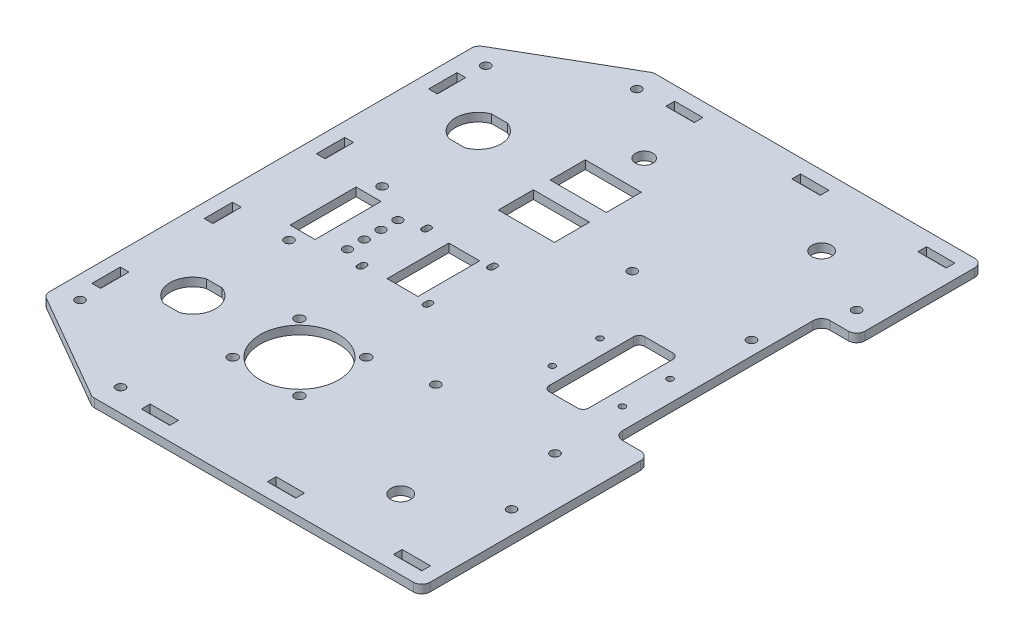
SolidWorks part; units mm, degrees
ref_plane "Front Plane" through (0, 0, 0) normal (0, 0, 1) x (1, 0, 0)
ref_plane "Top Plane" through (0, 0, 0) normal (0, 1, 0) x (1, 0, 0)
ref_plane "Right Plane" through (0, 0, 0) normal (1, 0, 0) x (0, 0, -1)
sketch "Sketch1" plane through (0, 0, 0) normal (0, 1, 0) x (1, 0, 0)
  line L0 (-85, 100) -> (85, 100) construction
  line L1 (-125, 100) -> (125, 100) construction
  line L2 (-125, 100) -> (-125, -100) construction
  line L3 (-125, -100) -> (125, -100) construction
  line L4 (125, 100) -> (125, -100) construction
  line L5 (85, 100) -> (125, 76.906) construction
  line L6 (125, 76.906) -> (125, -76.906) construction
  line L8 (-125, -76.906) -> (-125, 76.906) construction
  line L9 (-125, 76.906) -> (-85, 100) construction
  line L10 (-125, 0) -> (125, 0) construction
  line L11 (85, -100) -> (125, -76.906) construction
  line L12 (-85, -100) -> (85, -100) construction
  line L13 (-125, -76.906) -> (-85, -100) construction
  line L15 (-42.5, 100) -> (42.5, 100) construction
  line L16 (-42.5, 100) -> (-42.5, 65) construction
  line L17 (-42.5, 65) -> (42.5, 65) construction
  line L18 (42.5, 100) -> (42.5, 65) construction
  line L19 (42.5, -100) -> (42.5, -65) construction
  line L20 (-42.5, -65) -> (42.5, -65) construction
  line L21 (-42.5, -100) -> (-42.5, -65) construction
  line L22 (-42.5, -100) -> (42.5, -100) construction
  line L41 (32.5, -100) -> (32.5, 100)
  line L42 (-85, 100) -> (-125, 76.906)
  line L43 (-125, 76.906) -> (-125, -76.906)
  line L44 (-125, -76.906) -> (-85, -100)
  line L45 (-85, -100) -> (32.5, -100)
  line L46 (32.5, 100) -> (-85, 100)
  line L59 (-57.851, 11) -> (-68.851, 11) construction
  line L60 (-57.851, -11) -> (-57.851, 11) construction
  line L61 (-68.851, 11) -> (-68.851, -11) construction
  line L62 (-68.851, -11) -> (-57.851, -11) construction
  line L63 (-54.901, 12.05) -> (-54.901, 10.95) construction
  line L64 (-52.701, 10.95) -> (-52.701, 12.05) construction
  line L65 (-54.901, -10.95) -> (-54.901, -12.05) construction
  line L66 (-52.701, -12.05) -> (-52.701, -10.95) construction
  line L67 (-78.401, -10.95) -> (-78.401, -12.05) construction
  line L68 (-76.201, -12.05) -> (-76.201, -10.95) construction
  line L69 (-78.401, 12.05) -> (-78.401, 10.95) construction
  line L70 (-76.201, 10.95) -> (-76.201, 12.05) construction
  line L71 (-68.851, -11) -> (-57.851, -11)
  line L72 (-57.851, -11) -> (-57.851, 11)
  line L73 (-68.851, 11) -> (-68.851, -11)
  line L74 (-57.851, 11) -> (-68.851, 11)
  line L75 (-76.201, -12.05) -> (-76.201, -10.95)
  line L76 (-78.401, -10.95) -> (-78.401, -12.05)
  line L77 (-54.901, -10.95) -> (-54.901, -12.05)
  line L78 (-52.701, -12.05) -> (-52.701, -10.95)
  line L79 (-52.701, 10.95) -> (-52.701, 12.05)
  line L80 (-54.901, 12.05) -> (-54.901, 10.95)
  line L81 (-76.201, 10.95) -> (-76.201, 12.05)
  line L82 (-78.401, 12.05) -> (-78.401, 10.95)
  arc A16 (-52.701, 12.05) -> (-54.901, 12.05) centre (-53.801, 12.05) ccw construction
  arc A17 (-54.901, 10.95) -> (-52.701, 10.95) centre (-53.801, 10.95) ccw construction
  arc A18 (-52.701, -10.95) -> (-54.901, -10.95) centre (-53.801, -10.95) ccw construction
  arc A19 (-54.901, -12.05) -> (-52.701, -12.05) centre (-53.801, -12.05) ccw construction
  arc A20 (-76.201, -10.95) -> (-78.401, -10.95) centre (-77.301, -10.95) ccw construction
  arc A21 (-78.401, -12.05) -> (-76.201, -12.05) centre (-77.301, -12.05) ccw construction
  arc A22 (-76.201, 12.05) -> (-78.401, 12.05) centre (-77.301, 12.05) ccw construction
  arc A23 (-78.401, 10.95) -> (-76.201, 10.95) centre (-77.301, 10.95) ccw construction
  arc A24 (-78.401, -12.05) -> (-76.201, -12.05) centre (-77.301, -12.05) ccw
  arc A25 (-76.201, -10.95) -> (-78.401, -10.95) centre (-77.301, -10.95) ccw
  arc A26 (-54.901, -12.05) -> (-52.701, -12.05) centre (-53.801, -12.05) ccw
  arc A27 (-52.701, -10.95) -> (-54.901, -10.95) centre (-53.801, -10.95) ccw
  arc A28 (-54.901, 10.95) -> (-52.701, 10.95) centre (-53.801, 10.95) ccw
  arc A29 (-52.701, 12.05) -> (-54.901, 12.05) centre (-53.801, 12.05) ccw
  arc A30 (-78.401, 10.95) -> (-76.201, 10.95) centre (-77.301, 10.95) ccw
  arc A31 (-76.201, 12.05) -> (-78.401, 12.05) centre (-77.301, 12.05) ccw
  circle A32 centre (-98.226, -16.6) radius 1.6 construction
  circle A33 centre (-98.226, 16.6) radius 1.6 construction
  circle A34 centre (-98.226, -16.6) radius 1.6
  circle A35 centre (-98.226, 16.6) radius 1.6
  spline S0 degree 3 poles (-50.026, -38.959) (-50.026, -42.359) (-46.626, -42.359) (-46.626, -38.959) (-46.626, -35.559) (-50.026, -35.559) (-50.026, -38.959) (-50.026, -42.359) (-46.626, -42.359) knots -0.5 0 0 0 0.5 0.5 0.5 1 1 1 1.5 1.5 1.5 weights 1 0.333333 0.333333 1 0.333333 0.333333 1 0.333333 0.333333 only from (-50.026, -38.959) to (-50.026, -38.959) construction
  spline S1 degree 3 poles (-50.026, -62.759) (-50.026, -66.159) (-46.626, -66.159) (-46.626, -62.759) (-46.626, -59.359) (-50.026, -59.359) (-50.026, -62.759) (-50.026, -66.159) (-46.626, -66.159) knots -0.5 0 0 0 0.5 0.5 0.5 1 1 1 1.5 1.5 1.5 weights 1 0.333333 0.333333 1 0.333333 0.333333 1 0.333333 0.333333 only from (-50.026, -62.759) to (-50.026, -62.759) construction
  spline S2 degree 3 poles (-73.826, -62.759) (-73.826, -66.159) (-70.426, -66.159) (-70.426, -62.759) (-70.426, -59.359) (-73.826, -59.359) (-73.826, -62.759) (-73.826, -66.159) (-70.426, -66.159) knots -0.5 0 0 0 0.5 0.5 0.5 1 1 1 1.5 1.5 1.5 weights 1 0.333333 0.333333 1 0.333333 0.333333 1 0.333333 0.333333 only from (-73.826, -62.759) to (-73.826, -62.759) construction
  spline S3 degree 3 poles (-73.826, -38.959) (-73.826, -42.359) (-70.426, -42.359) (-70.426, -38.959) (-70.426, -35.559) (-73.826, -35.559) (-73.826, -38.959) (-73.826, -42.359) (-70.426, -42.359) knots -0.5 0 0 0 0.5 0.5 0.5 1 1 1 1.5 1.5 1.5 weights 1 0.333333 0.333333 1 0.333333 0.333333 1 0.333333 0.333333 only from (-73.826, -38.959) to (-73.826, -38.959) construction
  spline S4 degree 3 poles (-50.026, -38.959) (-50.026, -42.359) (-46.626, -42.359) (-46.626, -38.959) (-46.626, -35.559) (-50.026, -35.559) (-50.026, -38.959) (-50.026, -42.359) (-46.626, -42.359) knots -0.5 0 0 0 0.5 0.5 0.5 1 1 1 1.5 1.5 1.5 weights 1 0.333333 0.333333 1 0.333333 0.333333 1 0.333333 0.333333 only from (-50.026, -38.959) to (-50.026, -38.959)
  spline S5 degree 3 poles (-50.026, -62.759) (-50.026, -66.159) (-46.626, -66.159) (-46.626, -62.759) (-46.626, -59.359) (-50.026, -59.359) (-50.026, -62.759) (-50.026, -66.159) (-46.626, -66.159) knots -0.5 0 0 0 0.5 0.5 0.5 1 1 1 1.5 1.5 1.5 weights 1 0.333333 0.333333 1 0.333333 0.333333 1 0.333333 0.333333 only from (-50.026, -62.759) to (-50.026, -62.759)
  spline S6 degree 3 poles (-73.826, -62.759) (-73.826, -66.159) (-70.426, -66.159) (-70.426, -62.759) (-70.426, -59.359) (-73.826, -59.359) (-73.826, -62.759) (-73.826, -66.159) (-70.426, -66.159) knots -0.5 0 0 0 0.5 0.5 0.5 1 1 1 1.5 1.5 1.5 weights 1 0.333333 0.333333 1 0.333333 0.333333 1 0.333333 0.333333 only from (-73.826, -62.759) to (-73.826, -62.759)
  spline S7 degree 3 poles (-73.826, -38.959) (-73.826, -42.359) (-70.426, -42.359) (-70.426, -38.959) (-70.426, -35.559) (-73.826, -35.559) (-73.826, -38.959) (-73.826, -42.359) (-70.426, -42.359) knots -0.5 0 0 0 0.5 0.5 0.5 1 1 1 1.5 1.5 1.5 weights 1 0.333333 0.333333 1 0.333333 0.333333 1 0.333333 0.333333 only from (-73.826, -38.959) to (-73.826, -38.959)
  spline S8 degree 3 poles (-72.8629, -56.8847) (-73.764, -54.9949) (-74.226, -52.9527) (-74.226, -50.859) knots 0 0 0 0 1 1 1 1 weights 1 0.98357 0.98357 1 construction
  spline S9 degree 3 poles (-72.8629, -56.8847) (-72.5466, -57.548) (-72.1792, -58.1844) (-71.7629, -58.79) knots 0 0 0 0 1 1 1 1 weights 1 0.997939 0.997939 1 construction
  spline S10 degree 3 poles (-48.6891, -58.79) (-54.8172, -67.7043) (-65.6348, -67.7043) (-71.7629, -58.79) knots 0 0 0 0 1 1 1 1 weights 1 0.710999 0.710999 1 construction
  spline S11 degree 3 poles (-48.6891, -58.79) (-48.2728, -58.1844) (-47.9054, -57.548) (-47.5891, -56.8847) knots 0 0 0 0 1 1 1 1 weights 1 0.997939 0.997939 1 construction
  spline S12 degree 3 poles (-59.126, -36.9023) (-59.8586, -36.8445) (-60.5934, -36.8445) (-61.326, -36.9023) knots 0 0 0 0 1 1 1 1 weights 1 0.997939 0.997939 1 construction
  spline S13 degree 3 poles (-59.126, -36.9023) (-48.3419, -37.7522) (-42.9332, -47.1205) (-47.5891, -56.8847) knots 0 0 0 0 1 1 1 1 weights 1 0.710999 0.710999 1 construction
  spline S14 degree 3 poles (-74.226, -50.859) (-74.226, -43.1606) (-69.0006, -37.5072) (-61.326, -36.9023) knots 0 0 0 0 1 1 1 1 weights 1 0.822907 0.822907 1 construction
  spline S15 degree 3 poles (-72.8629, -56.8847) (-73.764, -54.9949) (-74.226, -52.9527) (-74.226, -50.859) knots 0 0 0 0 1 1 1 1 weights 1 0.98357 0.98357 1
  spline S16 degree 3 poles (-72.8629, -56.8847) (-72.5466, -57.548) (-72.1792, -58.1844) (-71.7629, -58.79) knots 0 0 0 0 1 1 1 1 weights 1 0.997939 0.997939 1
  spline S17 degree 3 poles (-48.6891, -58.79) (-54.8172, -67.7043) (-65.6348, -67.7043) (-71.7629, -58.79) knots 0 0 0 0 1 1 1 1 weights 1 0.710999 0.710999 1
  spline S18 degree 3 poles (-48.6891, -58.79) (-48.2728, -58.1844) (-47.9054, -57.548) (-47.5891, -56.8847) knots 0 0 0 0 1 1 1 1 weights 1 0.997939 0.997939 1
  spline S19 degree 3 poles (-59.126, -36.9023) (-59.8586, -36.8445) (-60.5934, -36.8445) (-61.326, -36.9023) knots 0 0 0 0 1 1 1 1 weights 1 0.997939 0.997939 1
  spline S20 degree 3 poles (-59.126, -36.9023) (-48.3419, -37.7522) (-42.9332, -47.1205) (-47.5891, -56.8847) knots 0 0 0 0 1 1 1 1 weights 1 0.710999 0.710999 1
  spline S21 degree 3 poles (-74.226, -50.859) (-74.226, -43.1606) (-69.0006, -37.5072) (-61.326, -36.9023) knots 0 0 0 0 1 1 1 1 weights 1 0.822907 0.822907 1
  point P4 (0, 100)
  point P6 (-125, 0)
  point P9 (0, 0)
  point P22 (0, 65)
  dimension "D1" = 250
  dimension "D2" = 200
  dimension "D3" = 60
  dimension "D4" = 60
  dimension "D5" = 40
  dimension "D6" = 85
  dimension "D7" = 35
  dimension "D8" = 20
extrude "Boss-Extrude1" add sketch "Sketch1" along normal blind 3
sketch "Sketch5" plane through (0, 3, 0) normal (0, 1, 0) x (1, 0, 0)
  line L0 (32.5, -40) -> (-32.5, -40) construction
  line L1 (32.5, 40) -> (-32.5, 40) construction
  line L2 (32.5, 40) -> (32.5, -40) construction
  line L4 (-32.5, 40) -> (-32.5, -40) construction
  line L10 (-32.5, 40) -> (-32.5, -40) construction
  line L14 (-27.5, 35) -> (15, 35) construction
  line L15 (-27.5, 35) -> (-27.5, -35) construction
  line L16 (-27.5, -35) -> (15, -35) construction
  line L17 (15, 35) -> (15, -35) construction
  circle A2 centre (-27.5, 35) radius 1.6
  circle A3 centre (15, 35) radius 1.6
  circle A4 centre (-27.5, -35) radius 1.6
  circle A5 centre (15, -35) radius 1.6
  point P4 (0, -40)
  point P6 (-32.5, 0)
  dimension "D4" = 3.2
  dimension "D1" = 65
  dimension "D2" = 80
  dimension "D5" = 5
  dimension "D3" = 5
  dimension "D6" = 5
  dimension "D7" = 17.5
extrude "Cut-Extrude2" cut sketch "Sketch5" against normal through all
sketch "Sketch8" plane through (0, 3, 0) normal (0, 1, 0) x (1, 0, 0)
  line L0 (-46.226, -50.859) -> (-74.226, -50.859) construction
  line L1 (-70.226, 42.5) -> (-50.226, 42.5)
  line L2 (-70.226, 42.5) -> (-70.226, 30)
  line L3 (-70.226, 30) -> (-50.226, 30)
  line L4 (-50.226, 42.5) -> (-50.226, 30)
  line L5 (-70.226, 48.5) -> (-50.226, 48.5)
  line L6 (-70.226, 48.5) -> (-70.226, 61)
  line L7 (-70.226, 61) -> (-50.226, 61)
  line L8 (-50.226, 48.5) -> (-50.226, 61)
  arc A0 (-47.5891, -56.8847) -> (-59.126, -36.9023) centre (-60.226, -50.859) ccw construction
  arc A1 (-61.326, -36.9023) -> (-74.226, -50.859) centre (-60.226, -50.859) ccw construction
  circle A2 centre (-60.226, 72) radius 3.1
  point P17 (-60.226, 30)
  point P18 (-60.226, -50.859)
  point P22 (-60.226, 61)
  dimension "D4" = 6.2
  dimension "D1" = 20
  dimension "D2" = 12.5
  dimension "D3" = 6
  dimension "D5" = 11
  dimension "D6" = 30
extrude "Cut-Extrude5" cut sketch "Sketch8" against normal through all
sketch "Sketch11" plane through (0, 3, 0) normal (0, 1, 0) x (1, 0, 0)
  line L0 (-101.0278, -43.259) -> (-95.4242, -43.259)
  line L1 (-101.0278, -58.459) -> (-95.4242, -58.459)
  line L2 (0, 0) -> (-125, 0) construction
  line L3 (-125, 76.906) -> (-125, -76.906) construction
  line L4 (-101.0278, 58.459) -> (-95.4242, 58.459)
  line L5 (-101.0278, 43.259) -> (-95.4242, 43.259)
  arc A0 (-101.0278, -43.259) -> (-101.0278, -58.459) centre (-98.226, -50.859) ccw
  arc A1 (-95.4242, -58.459) -> (-95.4242, -43.259) centre (-98.226, -50.859) ccw
  arc A2 (-101.0278, 43.259) -> (-101.0278, 58.459) centre (-98.226, 50.859) cw
  arc A3 (-95.4242, 58.459) -> (-95.4242, 43.259) centre (-98.226, 50.859) cw
  point P2 (-60.226, -50.859)
  dimension "D1" = 16.2
  dimension "D2" = 15.2
  dimension "D3" = 38
extrude "Cut-Extrude8" cut sketch "Sketch11" against normal through all contours L1 A0 L0 | A3 L4 A2 L5
sketch "Sketch12" plane through (0, 3, 0) normal (0, 1, 0) x (1, 0, 0)
  line L0 (-85, 9) -> (-85, 3) construction
  line L1 (-85, 3) -> (-85, -3) construction
  line L2 (-85, -3) -> (-85, -9) construction
  line L3 (-125, 76.906) -> (-125, -76.906) construction
  circle A0 centre (-85, 9) radius 1.55
  circle A1 centre (-85, 3) radius 1.55
  circle A2 centre (-85, -3) radius 1.55
  circle A3 centre (-85, -9) radius 1.55
  point P8 (-85, 0)
  dimension "D1" = 3.1
  dimension "D2" = 18
  dimension "D3" = 40
extrude "Cut-Extrude9" cut sketch "Sketch12" against normal through all
sketch "Sketch15" plane through (0, 3, 0) normal (0, 1, 0) x (1, 0, 0)
  line L0 (32.5, -100) -> (32.5, 100) construction
  line L1 (32.5, 55) -> (20, 55)
  line L2 (32.5, 55) -> (32.5, -19)
  line L3 (32.5, -19) -> (20, -19)
  line L4 (20, 55) -> (20, -19)
  line L5 (32.5, 100) -> (-85, 100) construction
  dimension "D1" = 74
  dimension "D2" = 12.5
  dimension "D3" = 45
extrude "Cut-Extrude12" cut sketch "Sketch15" against normal through all
sketch "Sketch13" plane through (0, 3, 0) normal (0, 1, 0) x (1, 0, 0)
  line L0 (32.5, 55) -> (32.5, 100) construction
  line L1 (32.5, 55) -> (20, 55) construction
  line L2 (32.5, -100) -> (32.5, -19) construction
  line L4 (-125, -76.906) -> (-85, -100) construction
  line L5 (-85, -100) -> (32.5, -100) construction
  line L6 (-125, 76.906) -> (-125, -76.906) construction
  line L7 (-85, 100) -> (-125, 76.906) construction
  line L8 (32.5, 100) -> (-85, 100) construction
  line L9 (-85, -100) -> (32.5, -100) construction
  circle A0 centre (24.5, 63) radius 1.6
  circle A1 centre (24.5, -60) radius 1.6
  circle A2 centre (-82.8564, -92) radius 1.6
  circle A3 centre (-117, -72.2872) radius 1.6
  circle A4 centre (-117, 72.2872) radius 1.6
  circle A5 centre (-82.8564, 92) radius 1.6
  dimension "D1" = 3.2
  dimension "D2" = 8
  dimension "D3" = 8
  dimension "D4" = 8
  dimension "D5" = 40
  dimension "D6" = 8
  dimension "D7" = 8
  dimension "D8" = 8
  dimension "D9" = 8
  dimension "D10" = 8
  dimension "D11" = 8
  dimension "D12" = 8
  dimension "D13" = 8
extrude "Cut-Extrude10" cut sketch "Sketch13" against normal up to next
sketch "Sketch14" plane through (0, 3, 0) normal (0, 1, 0) x (1, 0, 0)
  line L0 (-125, 76.906) -> (-125, -76.906) construction
  line L1 (-120, 65.05) -> (-116.9, 65.05)
  line L2 (-120, 65.05) -> (-120, 54.95)
  line L3 (-120, 54.95) -> (-116.9, 54.95)
  line L4 (-116.9, 65.05) -> (-116.9, 54.95)
  line L5 (-120, 25.05) -> (-116.9, 25.05)
  line L6 (-120, 25.05) -> (-120, 14.95)
  line L7 (-120, 14.95) -> (-116.9, 14.95)
  line L8 (-116.9, 25.05) -> (-116.9, 14.95)
  line L9 (-120, -14.95) -> (-116.9, -14.95)
  line L10 (-120, -14.95) -> (-120, -25.05)
  line L11 (-120, -25.05) -> (-116.9, -25.05)
  line L12 (-116.9, -14.95) -> (-116.9, -25.05)
  line L13 (-120, -54.95) -> (-116.9, -54.95)
  line L14 (-120, -54.95) -> (-120, -65.05)
  line L15 (-120, -65.05) -> (-116.9, -65.05)
  line L16 (-116.9, -54.95) -> (-116.9, -65.05)
  line L17 (-118.45, 14.95) -> (-118.45, -14.95) construction
  point P18 (-116.9, 20)
  point P19 (-116.9, -20)
  point P20 (-116.9, 60)
  point P21 (-116.9, -60)
  point P24 (-118.45, 0)
  dimension "D1" = 3.1
  dimension "D2" = 10.1
  dimension "D3" = 5
  dimension "D4" = 40
  dimension "D5" = 40
  dimension "D6" = 40
extrude "Cut-Extrude11" cut sketch "Sketch14" against normal through all
fillet "Fillet3" radius 3 10 edges at (32.5, 1.5, -100) (-85, 1.5, -100) (-125, 1.5, -76.906) (-125, 1.5, 76.906) (-85, 1.5, 100) (32.5, 1.5, 100) (20, 1.5, -55) (32.5, 1.5, -55) (20, 1.5, 19) (32.5, 1.5, 19)
sketch "Sketch16" plane through (0, 3, 0) normal (0, 1, 0) x (1, 0, 0)
  line L0 (-84.1962, -100) -> (29.5, -100) construction
  line L13 (17.4, -91.9) -> (27.5, -91.9)
  line L14 (17.4, -91.9) -> (17.4, -95)
  line L15 (17.4, -95) -> (27.5, -95)
  line L16 (27.5, -91.9) -> (27.5, -95)
  line L34 (0, 0) -> (-125, 0) construction
  line L35 (-1.65, 0) -> (1.65, 0) construction
  line L36 (-125, 75.1739) -> (-125, -75.1739) construction
  line L37 (-27.5, -91.9) -> (-27.5, -95)
  line L38 (-27.5, -91.9) -> (-17.4, -91.9)
  line L39 (-17.4, -91.9) -> (-17.4, -95)
  line L40 (-27.5, -95) -> (-17.4, -95)
  line L41 (-72.4, -91.9) -> (-72.4, -95)
  line L42 (-72.4, -91.9) -> (-62.3, -91.9)
  line L43 (-62.3, -91.9) -> (-62.3, -95)
  line L44 (-72.4, -95) -> (-62.3, -95)
  line L45 (17.4, 95) -> (27.5, 95)
  line L46 (27.5, 91.9) -> (27.5, 95)
  line L47 (17.4, 91.9) -> (27.5, 91.9)
  line L48 (17.4, 91.9) -> (17.4, 95)
  line L49 (-27.5, 91.9) -> (-17.4, 91.9)
  line L50 (-17.4, 91.9) -> (-17.4, 95)
  line L51 (-27.5, 95) -> (-17.4, 95)
  line L52 (-27.5, 91.9) -> (-27.5, 95)
  line L53 (-72.4, 91.9) -> (-62.3, 91.9)
  line L54 (-62.3, 91.9) -> (-62.3, 95)
  line L55 (-72.4, 95) -> (-62.3, 95)
  line L56 (-72.4, 91.9) -> (-72.4, 95)
  dimension "D1" = 10.1
  dimension "D2" = 3.1
  dimension "D3" = 5
  dimension "D5" = 3
extrude "Cut-Extrude13" cut sketch "Sketch16" against normal through all
sketch "Sketch17" plane through (0, 3, 0) normal (0, 1, 0) x (1, 0, 0)
  line L1 (-102.676, 11.75) -> (-93.776, 11.75)
  line L2 (-102.676, 11.75) -> (-102.676, -11.75)
  line L3 (-102.676, -11.75) -> (-93.776, -11.75)
  line L4 (-93.776, 11.75) -> (-93.776, -11.75)
  point P4 (-93.776, 0)
  point P7 (-98.226, -50.859)
  point P10 (-98.226, -11.75)
  dimension "D1" = 8.9
  dimension "D2" = 23.5
extrude "Cut-Extrude14" cut sketch "Sketch17" against normal through all
sketch "Sketch18" plane through (0, 3, 0) normal (0, 1, 0) x (1, 0, 0)
  line L0 (29.5, 100) -> (-84.1962, 100) construction
  line L1 (0, 0) -> (-125, 0) construction
  line L2 (-125, 75.1739) -> (-125, -75.1739) construction
  circle A0 centre (0, 75) radius 3.5
  circle A1 centre (0, -75) radius 3.5
  dimension "D1" = 7
  dimension "D2" = 25
extrude "Cut-Extrude15" cut sketch "Sketch18" against normal through all
sketch "Sketch19" plane through (0, 3, 0) normal (0, 1, 0) x (1, 0, 0)
  line L0 (0, 11) -> (0, -11) construction
  line L1 (-10, 20) -> (10, 20) construction
  line L2 (-10, 20) -> (-10, -20) construction
  line L3 (-10, -20) -> (10, -20) construction
  line L4 (10, 20) -> (10, -20) construction
  line L5 (-10, 11) -> (10, 11) construction
  line L6 (-10, 11) -> (-10, -11) construction
  line L7 (-10, -11) -> (10, -11) construction
  line L8 (10, 11) -> (10, -11) construction
  line L9 (10, 0) -> (-10, 0) construction
  line L10 (-10, -6) -> (-15, -6) construction
  line L11 (-10, 11) -> (-15, 11) construction
  line L12 (-10, 11) -> (-10, 6) construction
  line L13 (-10, 6) -> (-15, 6) construction
  line L14 (-15, 11) -> (-15, 6) construction
  line L15 (-15, -11) -> (-15, -6) construction
  line L16 (-10, -11) -> (-15, -11) construction
  line L17 (10, -11) -> (15, -11) construction
  line L18 (15, -11) -> (15, -6) construction
  line L19 (10, -6) -> (15, -6) construction
  line L20 (10, 6) -> (15, 6) construction
  line L21 (15, 11) -> (15, 6) construction
  line L22 (10, 11) -> (15, 11) construction
  line L23 (-5, 17) -> (5, 17)
  line L24 (7, 15) -> (7, -15)
  line L25 (-5, -17) -> (5, -17)
  line L26 (-7, 15) -> (-7, -15)
  line L27 (-7, -17) -> (7, -17) construction
  line L28 (-7, 17) -> (-7, -17) construction
  line L29 (7, 17) -> (7, -17) construction
  line L30 (-7, 17) -> (7, 17) construction
  circle A0 centre (-12.5, 8.5) radius 1.1
  circle A1 centre (-12.5, -8.5) radius 1.1
  circle A2 centre (12.5, -8.5) radius 1.1
  circle A3 centre (12.5, 8.5) radius 1.1
  arc A4 (-5, -17) -> (-7, -15) centre (-5, -15) cw
  arc A5 (7, -15) -> (5, -17) centre (5, -15) cw
  arc A6 (5, 17) -> (7, 15) centre (5, 15) cw
  arc A7 (-5, 17) -> (-7, 15) centre (-5, 15) ccw
  point P4 (-10, 0)
  point P6 (10, 0)
  point P7 (0, 0)
  point P8 (0, 20)
  point P23 (-12.5, 11)
  point P25 (-15, 8.5)
  dimension "D5" = 2.2
  dimension "D7" = 2
  dimension "D1" = 20
  dimension "D2" = 40
  dimension "D3" = 22
  dimension "D4" = 5
  dimension "D6" = 3
extrude "Cut-Extrude16" cut sketch "Sketch19" against normal through all
